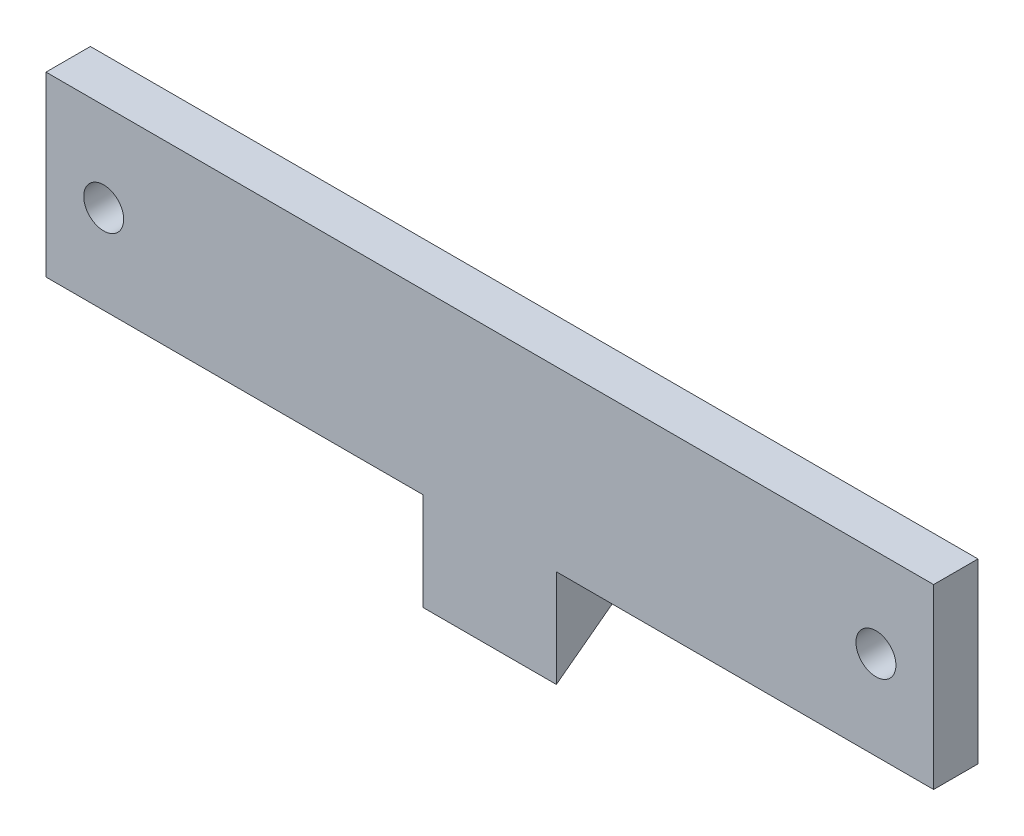
SolidWorks part; units mm, degrees
ref_plane "정면" through (0, 0, 0) normal (0, 0, 1) x (1, 0, 0)
ref_plane "윗면" through (0, 0, 0) normal (0, 1, 0) x (1, 0, 0)
ref_plane "우측면" through (0, 0, 0) normal (1, 0, 0) x (0, 0, -1)
sketch "스케치1" plane through (0, 0, 0) normal (0, 0, 1) x (1, 0, 0)
  line L1 (-50, 10) -> (50, 10)
  line L2 (-50, 10) -> (-50, -10)
  line L3 (-50, -10) -> (50, -10)
  line L4 (50, 10) -> (50, -10)
  line L5 (-50, 10) -> (50, -10) construction
  line L6 (-50, -10) -> (50, 10) construction
  point P0 (0, 0)
  dimension "D1" = 20
  dimension "D2" = 100
extrude "보스-돌출1" add sketch "스케치1" along normal blind 5
hole_wizard "M4 여유 구멍1" positions "스케치2" profile "스케치3" hole size "M4" standard "KS" end condition through all
sketch "스케치2" plane through (0, 0, 5) normal (0, 0, 1) x (1, 0, 0)
  line L0 (-50, 10) -> (-50, -10) construction
  line L2 (50, -10) -> (50, 10) construction
  line L3 (-50, -10) -> (50, -10) construction
  point P0 (-43.5, 0)
  point P2 (43.5, 0)
  dimension "D1" = 87
  dimension "D2" = 6.5
  dimension "D3" = 6.5
  dimension "D4" = 10
sketch "스케치3" plane through (-43.5, 0, 5) normal (1, 0, 0) x (0, -1, 0)
  line L0 (0, 0) -> (0, 5)
  line L1 (0, 5) -> (2.25, 5)
  line L2 (2.25, 5) -> (2.25, 0)
  line L5 (2.25, 0) -> (0, 0)
  line L11 (0, -6.35) -> (0, 107.95) construction
  dimension "관통 구멍 지름" = 4.5
  dimension "관통 구멍 깊이" = 5
sketch "스케치4" plane through (0, -10, 0) normal (0, 1, 0) x (1, 0, 0)
  line L0 (50, 0) -> (-50, 0) construction
  line L1 (-7.5, -5) -> (7.5, -5)
  line L2 (-7.5, -5) -> (-7.5, 0)
  line L3 (-7.5, 0) -> (7.5, 0)
  line L4 (7.5, -5) -> (7.5, 0)
  line L5 (-7.5, -5) -> (7.5, 0) construction
  line L6 (-7.5, 0) -> (7.5, -5) construction
  line L7 (50, -5) -> (-50, -5) construction
  point P0 (0, -2.5)
  point P7 (5.1671, -5)
  dimension "D1" = 15
  dimension "D2" = 0
extrude "보스-돌출2" add sketch "스케치4" against normal blind 5
sketch "스케치5" plane through (0, 0, 0) normal (0, 0, 1) x (1, 0, 0)
  line L1 (-7.5, -15) -> (7.5, -15)
  line L2 (-7.5, -15) -> (-7.5, -10)
  line L3 (-7.5, -10) -> (7.5, -10)
  line L4 (7.5, -15) -> (7.5, -10)
extrude "보스-돌출3" add sketch "스케치5" against normal blind 7.35
sketch "스케치6" plane through (0, -15, 0) normal (0, -1, 0) x (1, 0, 0)
  line L0 (-7.5, -7.35) -> (-7.5, 5) construction
  line L1 (-7.5, 5) -> (7.5, 5)
  line L2 (-7.5, 5) -> (-7.5, -3)
  line L3 (-7.5, -3) -> (7.5, -3)
  line L4 (7.5, 5) -> (7.5, -3)
  line L5 (-7.5, 5) -> (7.5, 5) construction
  line L6 (7.5, 5) -> (7.5, -7.35) construction
  dimension "D1" = 8
extrude "보스-돌출4" add sketch "스케치6" along normal blind 6
sketch "스케치7" plane through (7.5, 0, 0) normal (1, 0, 0) x (0, 0, -1)
  line L0 (3, -21) -> (-5, -21)
  line L1 (-5, -21) -> (3, -15)
  line L2 (3, -15) -> (3, -21)
extrude "컷-돌출1" cut sketch "스케치7" against normal through all
